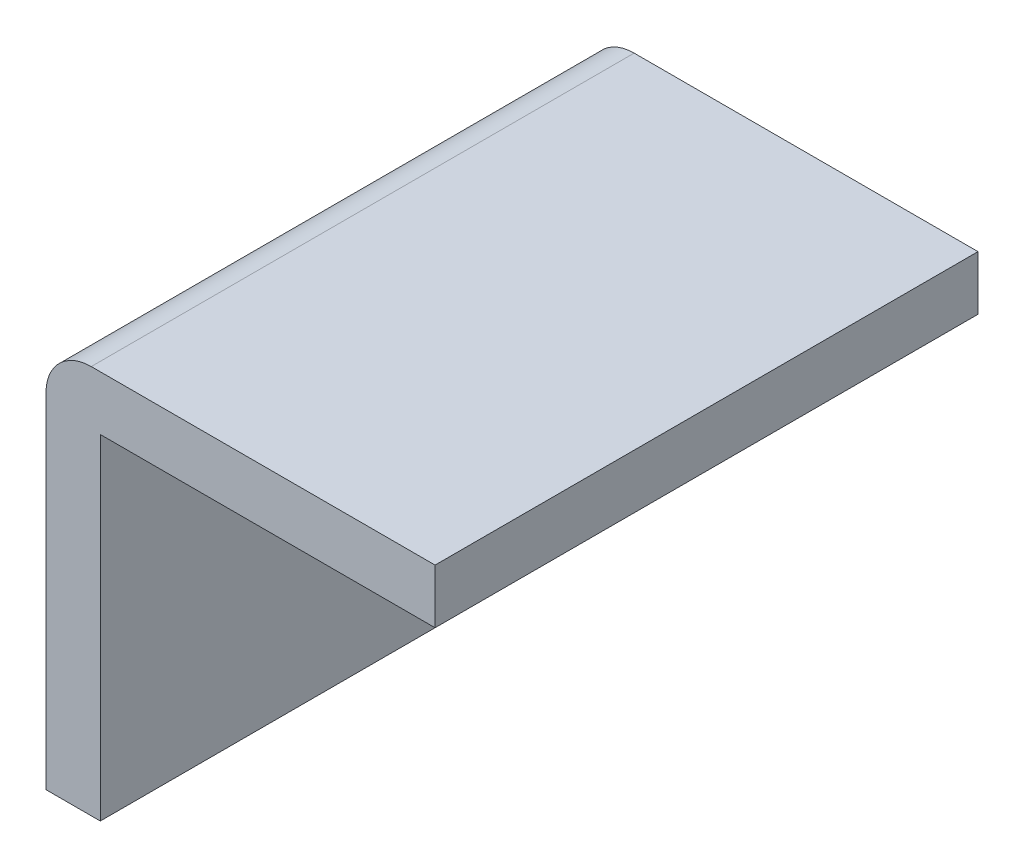
SolidWorks part; units mm, degrees
material "Acrilico TEC"
ref_plane "Front Plane" through (0, 0, 0) normal (0, 0, 1) x (1, 0, 0)
ref_plane "Top Plane" through (0, 0, 0) normal (0, 1, 0) x (1, 0, 0)
ref_plane "Right Plane" through (0, 0, 0) normal (1, 0, 0) x (0, 0, -1)
sketch "Sketch1" plane through (0, 0, 0) normal (0, 0, 1) x (1, 0, 0)
  line L0 (0, 0) -> (0, 19)
  line L1 (1, 20) -> (20, 20)
  line L2 (1.5, 0) -> (1.5, 18.5)
  line L3 (1.5, 18.5) -> (20, 18.5)
  line L4 (-1.5, 0) -> (-1.5, 19)
  line L5 (1, 21.5) -> (20, 21.5)
  line L6 (20, 21.5) -> (20, 18.5)
  line L7 (-1.5, 0) -> (1.5, 0)
  arc A0 (0, 19) -> (1, 20) centre (1, 19) cw
  arc A1 (1.5, 18.5) -> (1.5, 18.5) centre (1.5, 18.5) cw
  arc A2 (-1.5, 19) -> (1, 21.5) centre (1, 19) cw
  point P6 (0, 20)
  dimension "D3" = 1
  dimension "D1" = 20
  dimension "D2" = 20
  dimension "D4" = 1.5
  dimension "D5" = 1.5
extrude "Boss-Extrude1" add sketch "Sketch1" along normal blind 30 contours A0 L0 L7 L2 L3 L6 L1 | A2 L4 L7 L0 A0 L1 L6 L5
hole_wizard "Ø2.0mm Clearance Dowel Hole1" positions "Sketch2" profile "Sketch3" hole size "Ø2.0" standard "ISO"
sketch "Sketch2" plane through (-44.9294, 18.5, -46) normal (0, -1, 0) x (-1, 0, 0)
  point P0 (-26.9294, -76.5)
  point P1 (-26.9294, -70.5)
sketch "Sketch3" plane through (-18, 18.5, 30.5) normal (1, 0, 0) x (0, 0, -1)
  line L0 (0, 0) -> (0, 3)
  line L1 (0, 3) -> (1, 3)
  line L2 (1, 3) -> (1, 0)
  line L3 (1, 0) -> (0, 0)
  line L4 (0, -6.35) -> (0, 107.95) construction
  dimension "Thru Hole Dia." = 2
  dimension "Thru Hole Depth" = 3
